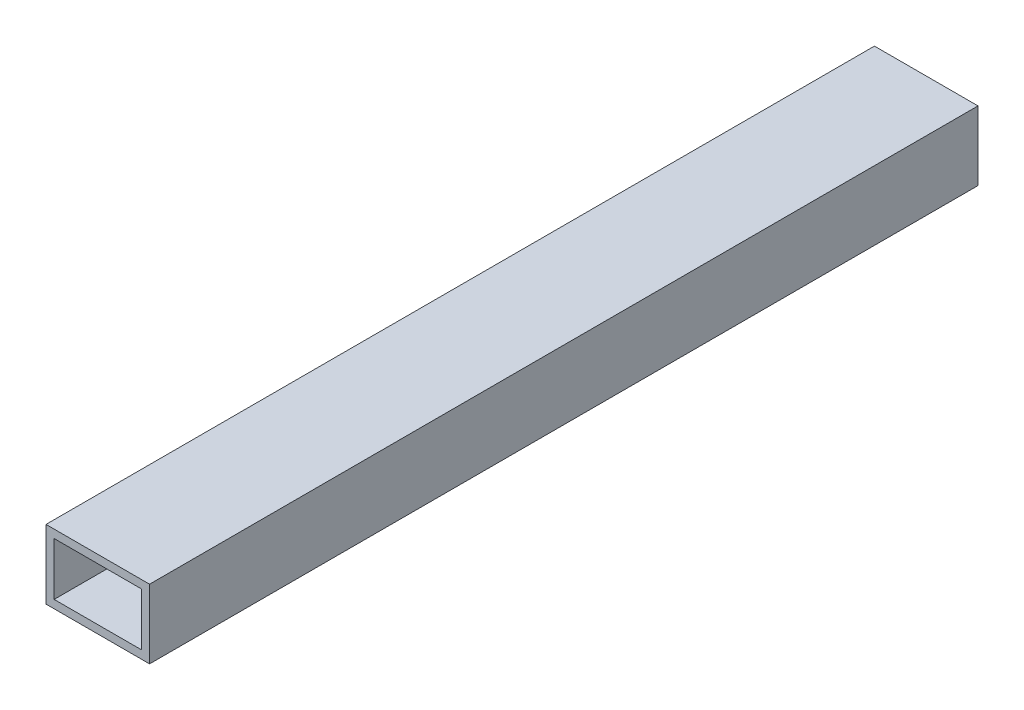
SolidWorks part; units mm, degrees
ref_plane "Front Plane" through (0, 0, 0) normal (0, 0, 1) x (1, 0, 0)
ref_plane "Top Plane" through (0, 0, 0) normal (0, 1, 0) x (1, 0, 0)
ref_plane "Right Plane" through (0, 0, 0) normal (1, 0, 0) x (0, 0, -1)
sketch "Sketch2" plane through (0, 0, 0) normal (0, 0, 1) x (1, 0, 0)
  line L1 (-38.1, -25.4) -> (38.1, -25.4)
  line L2 (-38.1, -25.4) -> (-38.1, 25.4)
  line L3 (-38.1, 25.4) -> (38.1, 25.4)
  line L4 (38.1, -25.4) -> (38.1, 25.4)
  line L5 (-38.1, -25.4) -> (38.1, 25.4) construction
  line L6 (-38.1, 25.4) -> (38.1, -25.4) construction
  line L7 (-32.1, -19.4) -> (32.1, -19.4)
  line L8 (-32.1, -19.4) -> (-32.1, 19.4)
  line L9 (-32.1, 19.4) -> (32.1, 19.4)
  line L10 (32.1, -19.4) -> (32.1, 19.4)
  line L11 (-32.1, -19.4) -> (32.1, 19.4) construction
  line L12 (-32.1, 19.4) -> (32.1, -19.4) construction
  point P0 (0, 0)
  point P6 (0, 0)
  dimension "D1" = 76.2
  dimension "D2" = 50.8
  dimension "D3" = 6
  dimension "D4" = 6
extrude "Boss-Extrude1" add sketch "Sketch2" along normal blind 609.6
